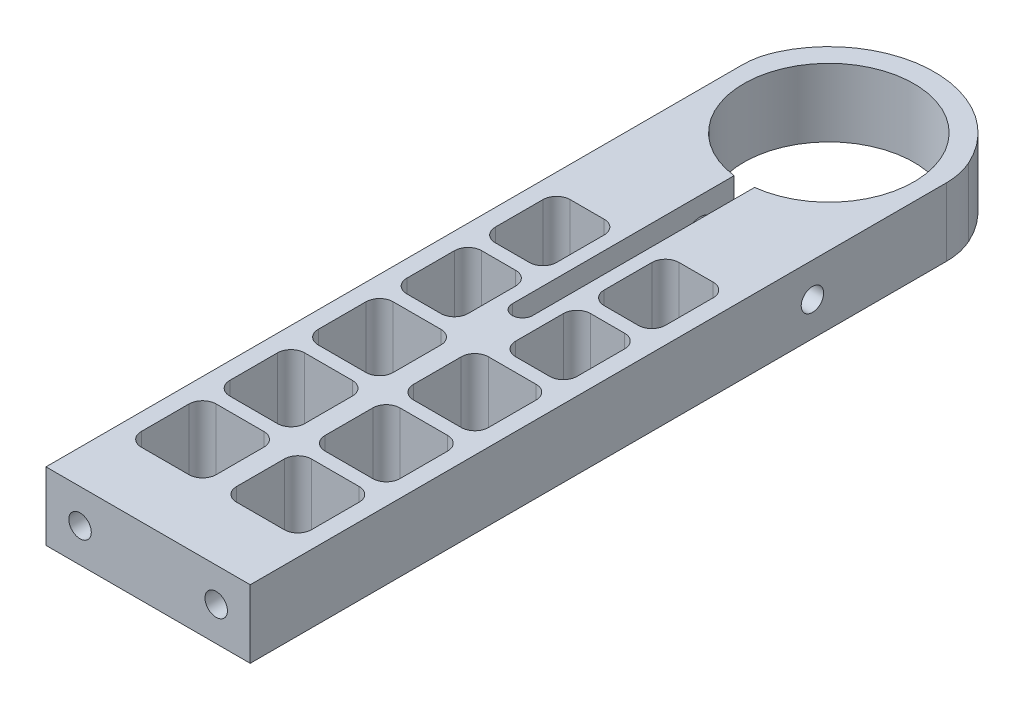
SolidWorks part; units mm, degrees
material "3.1355 (EN-AW 2024)"
ref_plane "Спереди" through (0, 0, 0) normal (0, 0, 1) x (1, 0, 0)
ref_plane "Сверху" through (0, 0, 0) normal (0, 1, 0) x (1, 0, 0)
ref_plane "Справа" through (0, 0, 0) normal (1, 0, 0) x (0, 0, -1)
sketch "Эскиз1" plane through (0, 0, 0) normal (0, 1, 0) x (1, 0, 0)
  line L0 (0, 0) -> (0, -100) construction
  line L1 (-15.5, 0) -> (-15.5, -100)
  line L2 (-15.5, -100) -> (15.5, -100)
  line L3 (15.5, -100) -> (15.5, 0)
  circle A0 centre (0, 0) radius 12.5
  arc A1 (15.5, 0) -> (-15.5, 0) centre (0, 0) ccw
  dimension "D1" = 25
  dimension "D2" = 31
  dimension "D3" = 100
extrude "Бобышка-Вытянуть1" add sketch "Эскиз1" along normal blind 10
sketch "Эскиз6" plane through (0, 10, 0) normal (0, 1, 0) x (1, 0, 0)
  line L0 (0, -12.5) -> (0, -27.5) construction
  line L1 (-15.5, -100) -> (15.5, -100) construction
  line L2 (0, -100) -> (0, -90) construction
  line L3 (-1.5, -12.4097) -> (-1.5, -26)
  line L4 (1.5, -12.4097) -> (1.5, -26)
  line L5 (-1.5, -12.5) -> (-1.5, -27.5) construction
  line L6 (1.5, -12.5) -> (1.5, -27.5) construction
  line L7 (-1.5, -27.5) -> (1.5, -27.5) construction
  line L9 (-1.5, -42.5) -> (-1.5, -49.5)
  line L10 (-10.5, -51.5) -> (-3.5, -51.5)
  line L11 (-12.5, -42.5) -> (-12.5, -49.5)
  line L12 (-10.5, -40.5) -> (-3.5, -40.5)
  line L13 (-1.5, -55.5) -> (-1.5, -62.5)
  line L14 (-10.5, -64.5) -> (-3.5, -64.5)
  line L15 (-12.5, -55.5) -> (-12.5, -62.5)
  line L16 (-10.5, -53.5) -> (-3.5, -53.5)
  line L17 (-1.5, -68.5) -> (-1.5, -75.5)
  line L18 (-10.5, -77.5) -> (-3.5, -77.5)
  line L19 (-12.5, -68.5) -> (-12.5, -75.5)
  line L20 (-10.5, -66.5) -> (-3.5, -66.5)
  line L21 (-1.5, -81.5) -> (-1.5, -88.5)
  line L22 (-10.5, -90.5) -> (-3.5, -90.5)
  line L23 (-12.5, -81.5) -> (-12.5, -88.5)
  line L24 (-10.5, -79.5) -> (-3.5, -79.5)
  line L25 (-1.5, -29.5) -> (-1.5, -42.5) construction
  line L26 (12.5, -38.5) -> (1.5, -27.5) construction
  line L27 (12.5, -27.5) -> (1.5, -38.5) construction
  line L28 (1.5, -29.5) -> (1.5, -42.5) construction
  line L29 (1.5, -29.5) -> (1.5, -36.5)
  line L30 (10.5, -38.5) -> (3.5, -38.5)
  line L31 (-12.5, 0) -> (-12.5, -100)
  line L32 (-12.5, -29.5) -> (-12.5, -36.5)
  line L33 (10.5, -27.5) -> (3.5, -27.5)
  line L36 (-10.5, -27.5) -> (-3.5, -27.5)
  line L37 (12.5, -29.5) -> (12.5, -36.5)
  line L38 (-10.5, -38.5) -> (-3.5, -38.5)
  line L39 (-1.5, -29.5) -> (-1.5, -36.5)
  line L40 (-12.5, -27.5) -> (-1.5, -38.5) construction
  line L41 (-12.5, -38.5) -> (-1.5, -27.5) construction
  line L42 (10.5, -79.5) -> (3.5, -79.5)
  line L43 (12.5, -81.5) -> (12.5, -88.5)
  line L44 (10.5, -90.5) -> (3.5, -90.5)
  line L45 (1.5, -81.5) -> (1.5, -88.5)
  line L46 (10.5, -66.5) -> (3.5, -66.5)
  line L47 (12.5, -68.5) -> (12.5, -75.5)
  line L48 (10.5, -77.5) -> (3.5, -77.5)
  line L49 (1.5, -68.5) -> (1.5, -75.5)
  line L50 (10.5, -53.5) -> (3.5, -53.5)
  line L51 (12.5, -55.5) -> (12.5, -62.5)
  line L52 (10.5, -64.5) -> (3.5, -64.5)
  line L53 (1.5, -55.5) -> (1.5, -62.5)
  line L54 (10.5, -40.5) -> (3.5, -40.5)
  line L55 (12.5, -42.5) -> (12.5, -49.5)
  line L56 (10.5, -51.5) -> (3.5, -51.5)
  line L57 (1.5, -42.5) -> (1.5, -49.5)
  circle A0 centre (0, 0) radius 12.5 construction
  arc A1 (-1.5, -12.4097) -> (1.5, -12.4097) centre (0, 0) ccw
  arc A2 (-12.5, -29.5) -> (-10.5, -27.5) centre (-10.5, -29.5) cw
  arc A3 (-12.5, -36.5) -> (-10.5, -38.5) centre (-10.5, -36.5) ccw
  arc A4 (-3.5, -38.5) -> (-1.5, -36.5) centre (-3.5, -36.5) ccw
  arc A5 (-1.5, -29.5) -> (-3.5, -27.5) centre (-3.5, -29.5) ccw
  arc A6 (-1.5, -26) -> (1.5, -26) centre (0, -26) ccw
  arc A7 (-1.5, -42.5) -> (-3.5, -40.5) centre (-3.5, -42.5) ccw
  arc A8 (-3.5, -51.5) -> (-1.5, -49.5) centre (-3.5, -49.5) ccw
  arc A9 (-12.5, -49.5) -> (-10.5, -51.5) centre (-10.5, -49.5) ccw
  arc A10 (-12.5, -42.5) -> (-10.5, -40.5) centre (-10.5, -42.5) cw
  arc A11 (-1.5, -55.5) -> (-3.5, -53.5) centre (-3.5, -55.5) ccw
  arc A12 (-3.5, -64.5) -> (-1.5, -62.5) centre (-3.5, -62.5) ccw
  arc A13 (-12.5, -62.5) -> (-10.5, -64.5) centre (-10.5, -62.5) ccw
  arc A14 (-12.5, -55.5) -> (-10.5, -53.5) centre (-10.5, -55.5) cw
  arc A15 (-1.5, -68.5) -> (-3.5, -66.5) centre (-3.5, -68.5) ccw
  arc A16 (-3.5, -77.5) -> (-1.5, -75.5) centre (-3.5, -75.5) ccw
  arc A17 (-12.5, -75.5) -> (-10.5, -77.5) centre (-10.5, -75.5) ccw
  arc A18 (-12.5, -68.5) -> (-10.5, -66.5) centre (-10.5, -68.5) cw
  arc A19 (-1.5, -81.5) -> (-3.5, -79.5) centre (-3.5, -81.5) ccw
  arc A20 (-3.5, -90.5) -> (-1.5, -88.5) centre (-3.5, -88.5) ccw
  arc A21 (-12.5, -88.5) -> (-10.5, -90.5) centre (-10.5, -88.5) ccw
  arc A22 (-12.5, -81.5) -> (-10.5, -79.5) centre (-10.5, -81.5) cw
  arc A23 (12.5, -81.5) -> (10.5, -79.5) centre (10.5, -81.5) ccw
  arc A24 (12.5, -88.5) -> (10.5, -90.5) centre (10.5, -88.5) cw
  arc A25 (3.5, -90.5) -> (1.5, -88.5) centre (3.5, -88.5) cw
  arc A26 (1.5, -81.5) -> (3.5, -79.5) centre (3.5, -81.5) cw
  arc A27 (12.5, -68.5) -> (10.5, -66.5) centre (10.5, -68.5) ccw
  arc A28 (12.5, -75.5) -> (10.5, -77.5) centre (10.5, -75.5) cw
  arc A29 (3.5, -77.5) -> (1.5, -75.5) centre (3.5, -75.5) cw
  arc A30 (1.5, -68.5) -> (3.5, -66.5) centre (3.5, -68.5) cw
  arc A31 (12.5, -55.5) -> (10.5, -53.5) centre (10.5, -55.5) ccw
  arc A32 (12.5, -62.5) -> (10.5, -64.5) centre (10.5, -62.5) cw
  arc A33 (3.5, -64.5) -> (1.5, -62.5) centre (3.5, -62.5) cw
  arc A34 (1.5, -55.5) -> (3.5, -53.5) centre (3.5, -55.5) cw
  arc A35 (12.5, -42.5) -> (10.5, -40.5) centre (10.5, -42.5) ccw
  arc A36 (12.5, -49.5) -> (10.5, -51.5) centre (10.5, -49.5) cw
  arc A37 (3.5, -51.5) -> (1.5, -49.5) centre (3.5, -49.5) cw
  arc A38 (1.5, -42.5) -> (3.5, -40.5) centre (3.5, -42.5) cw
  arc A39 (1.5, -29.5) -> (3.5, -27.5) centre (3.5, -29.5) cw
  arc A40 (3.5, -38.5) -> (1.5, -36.5) centre (3.5, -36.5) cw
  arc A41 (12.5, -36.5) -> (10.5, -38.5) centre (10.5, -36.5) cw
  arc A42 (12.5, -29.5) -> (10.5, -27.5) centre (10.5, -29.5) ccw
  point P13 (-7, -33)
  point P152 (7, -33)
  dimension "D7" = 2
  dimension "D8" = 5
  dimension "D1" = 15
  dimension "D2" = 10
  dimension "D5" = 3
  dimension "D9" = 13
  dimension "D3" = 1.5
  dimension "D4" = 1.5
extrude "Вырез-Вытянуть5" cut sketch "Эскиз6" against normal through all
sketch "Эскиз7" plane through (15.5, 0, 0) normal (1, 0, 0) x (0, 0, -1)
  line L0 (-12.4097, 5) -> (-17.4097, 5) construction
  line L1 (-12.4097, 0) -> (-12.4097, 10) construction
  dimension "D1" = 5
hole_wizard "Отверстие обработанное метчиком M4x0.71" positions "Эскиз9" profile "Эскиз8" tap size "M4x0.7" standard "Ansi Metric"
sketch "Эскиз9" plane through (1.5, 0, 0) normal (-1, 0, 0) x (0, 0, 1)
  point P0 (17.4097, 5)
sketch "Эскиз8" plane through (1.5, 5, 17.4097) normal (0, 1, 0) x (0, 0, 1)
  line L0 (0, 0) -> (0, 14)
  line L1 (0, 14) -> (1.65, 14)
  line L2 (1.65, 14) -> (1.65, 0)
  line L5 (1.65, 0) -> (0, 0)
  line L11 (0, -6.35) -> (0, 107.95) construction
  dimension "Диаметр проходного сверла" = 3.3
  dimension "Глубина проходного сверла" = 14
cosmetic thread "Отверстие резьбы1" parameters "D2"=4
hole_wizard "Цековка для винта с внутренним шестигранником M41" positions "Эскиз11" profile "Эскиз10" counterbore size "M4" standard "Ansi Metric"
sketch "Эскиз11" plane through (-15.5, 0, 0) normal (-1, 0, 0) x (0, 0, 1)
  point P0 (17.4097, 5)
sketch "Эскиз10" plane through (-15.5, 5, 17.4097) normal (0, 1, 0) x (0, 0, 1)
  line L0 (0, 0) -> (0, 14)
  line L1 (0, 14) -> (2.25, 14)
  line L3 (2.25, 14) -> (2.25, 4.5)
  line L4 (2.25, 4.5) -> (4, 4.5)
  line L5 (4, 4.5) -> (4, 0)
  line L7 (4, 0) -> (0, 0)
  line L11 (0, -6.35) -> (0, 107.95) construction
  dimension "Диаметр сквозного отверстия" = 4.5
  dimension "Глубина сквозного отверстия" = 14
  dimension "Диаметр цековки" = 8
  dimension "Глубина цековки" = 4.5
sketch "Эскиз12" plane through (0, 10, 0) normal (0, 1, 0) x (1, 0, 0)
  line L2 (-15, 0) -> (-15, -100)
  line L3 (-15, 3.9051) -> (-15, -100)
  line L4 (-15, -100) -> (-15.5, -100)
  line L5 (15, -100) -> (15, 0)
  line L6 (15, -100) -> (15, 3.9051)
  line L7 (-15.5, -100) -> (-15.5, 0)
  line L8 (15, -100) -> (15.5, -100)
  line L9 (15.5, -100) -> (15.5, 0)
  arc A0 (15.5, 0) -> (-15.5, 0) centre (0, 0) ccw construction
  arc A1 (15.5, 0) -> (15, 3.9051) centre (0, 0) ccw
  arc A2 (-15, 3.9051) -> (-15.5, 0) centre (0, 0) ccw
  dimension "D1" = 0.5
  dimension "D2" = 0.5
extrude "Вырез-Вытянуть6" cut sketch "Эскиз12" against normal blind 10
fillet "Скругление1" radius 10 2 edges at (-15, 5, -3.9051) (15, 5, -3.9051)
hole_wizard "Отверстие обработанное метчиком M4x0.72" positions "Эскиз14" profile "Эскиз13" tap size "M4x0.7" standard "Ansi Metric"
sketch "Эскиз14" plane through (0, 0, 100) normal (0, 0, 1) x (1, 0, 0)
  point P0 (-9.9983, 5)
  point P3 (10.0017, 5)
cosmetic thread "Отверстие резьбы2" parameters "D1"=9.8649, "D2"=4
cosmetic thread "Отверстие резьбы3" parameters "D1"=9.8625, "D2"=4
sketch "Эскиз13" plane through (-9.9983, 5, 100) normal (1, 0, 0) x (0, -1, 0)
  line L0 (0, 0) -> (0, 10.9914)
  line L1 (0, 10.9914) -> (1.65, 10)
  line L2 (1.65, 10) -> (1.65, 0)
  line L5 (1.65, 0) -> (0, 0)
  line L10 (0, 10.9914) -> (-1.65, 10) construction
  line L11 (0, -6.35) -> (0, 107.95) construction
  dimension "Диаметр сверла" = 3.3
  dimension "Глубина сверла" = 10
  dimension "Угол заточки сверла" = 118
sketch "Эскиз16" plane through (0, 10, 0) normal (0, 1, 0) x (1, 0, 0)
  line L0 (0, -26) -> (0, -45) construction
  line L1 (1.5, -26) -> (1.5, -45)
  line L2 (-1.5, -26) -> (-1.5, -45)
  line L3 (-1.5, -12.4097) -> (-1.5, -26) construction
  arc A0 (1.5, -26) -> (-1.5, -26) centre (0, -26) ccw
  arc A1 (-1.5, -45) -> (1.5, -45) centre (0, -45) ccw
  arc A2 (-1.5, -26) -> (1.5, -26) centre (0, -26) ccw construction
  point P4 (0, -35.5)
  point P11 (0, -27.5)
  point P12 (0, -46.5)
  dimension "D1" = 19
extrude "Вырез-Вытянуть7" cut sketch "Эскиз16" against normal through all
sketch "Эскиз17" plane through (0, 10, 0) normal (0, 1, 0) x (1, 0, 0)
  line L0 (-1.5, -29.5) -> (-1.5, -36.5)
  line L1 (-1.5, -42.5) -> (-1.5, -49.5)
  line L2 (-3.5, -29.5) -> (-3.5, -36.5)
  line L3 (-3.5, -42.5) -> (-3.5, -49.5)
  line L4 (-3.5, -27.5) -> (-10.5, -27.5) construction
  line L5 (-10.5, -38.5) -> (-3.5, -38.5) construction
  line L6 (-3.5, -40.5) -> (-10.5, -40.5) construction
  line L7 (-10.5, -51.5) -> (-3.5, -51.5) construction
  line L8 (-3.5, -27.5) -> (-5.5, -27.5)
  line L9 (-3.5, -40.5) -> (-5.5, -40.5)
  line L10 (-5.5, -38.5) -> (-3.5, -38.5)
  line L11 (-5.5, -51.5) -> (-3.5, -51.5)
  line L12 (0, 0) -> (0, -20.32) construction
  line L13 (5.5, -51.5) -> (3.5, -51.5)
  line L14 (5.5, -38.5) -> (3.5, -38.5)
  line L15 (3.5, -40.5) -> (5.5, -40.5)
  line L16 (3.5, -27.5) -> (5.5, -27.5)
  line L17 (3.5, -42.5) -> (3.5, -49.5)
  line L18 (3.5, -29.5) -> (3.5, -36.5)
  line L19 (1.5, -42.5) -> (1.5, -49.5)
  line L20 (1.5, -29.5) -> (1.5, -36.5)
  arc A0 (-3.5, -29.5) -> (-5.5, -27.5) centre (-5.5, -29.5) ccw
  arc A1 (-3.5, -36.5) -> (-5.5, -38.5) centre (-5.5, -36.5) cw
  arc A2 (-3.5, -42.5) -> (-5.5, -40.5) centre (-5.5, -42.5) ccw
  arc A3 (-3.5, -49.5) -> (-5.5, -51.5) centre (-5.5, -49.5) cw
  arc A5 (-3.5, -51.5) -> (-1.5, -49.5) centre (-3.5, -49.5) ccw
  arc A7 (-3.5, -38.5) -> (-1.5, -36.5) centre (-3.5, -36.5) ccw
  arc A9 (-1.5, -29.5) -> (-3.5, -27.5) centre (-3.5, -29.5) ccw
  arc A11 (-1.5, -42.5) -> (-3.5, -40.5) centre (-3.5, -42.5) ccw
  arc A12 (1.5, -42.5) -> (3.5, -40.5) centre (3.5, -42.5) cw
  arc A13 (1.5, -29.5) -> (3.5, -27.5) centre (3.5, -29.5) cw
  arc A14 (3.5, -38.5) -> (1.5, -36.5) centre (3.5, -36.5) cw
  arc A15 (3.5, -51.5) -> (1.5, -49.5) centre (3.5, -49.5) cw
  arc A16 (3.5, -49.5) -> (5.5, -51.5) centre (5.5, -49.5) ccw
  arc A17 (3.5, -42.5) -> (5.5, -40.5) centre (5.5, -42.5) cw
  arc A18 (3.5, -36.5) -> (5.5, -38.5) centre (5.5, -36.5) ccw
  arc A19 (3.5, -29.5) -> (5.5, -27.5) centre (5.5, -29.5) cw
  dimension "D1" = 2
extrude "Бобышка-Вытянуть2" add sketch "Эскиз17" against normal through all
equation "\"D2@Эскиз1\"=\"D1@Эскиз1\"+6"
